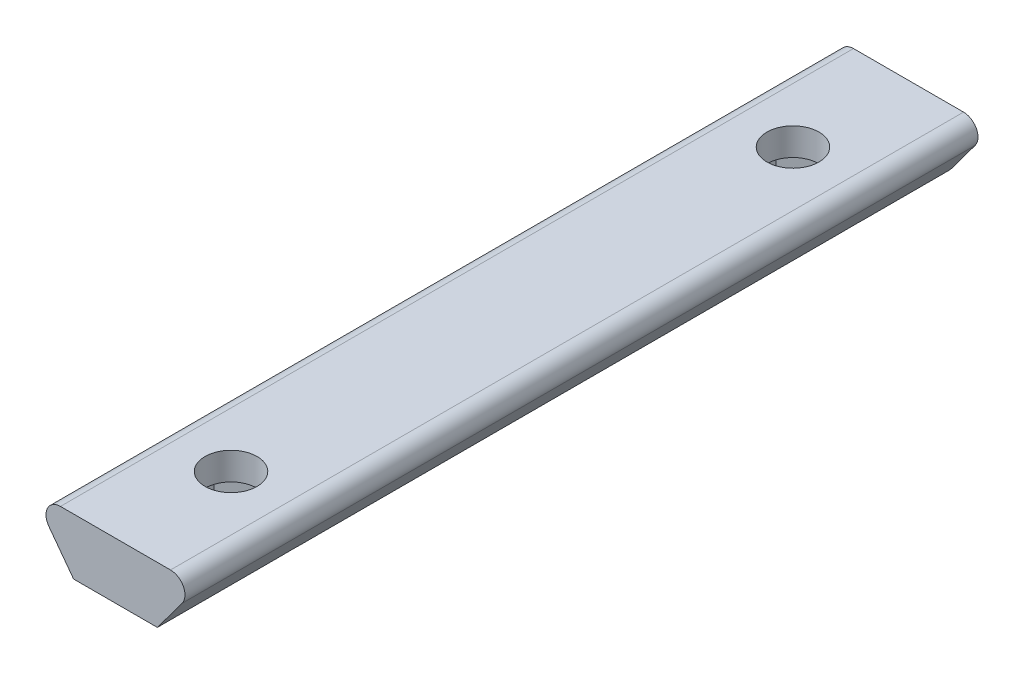
SolidWorks part; units mm, degrees
ref_plane "Front Plane" through (0, 0, 0) normal (0, 0, 1) x (1, 0, 0)
ref_plane "Top Plane" through (0, 0, 0) normal (0, 1, 0) x (1, 0, 0)
ref_plane "Right Plane" through (0, 0, 0) normal (1, 0, 0) x (0, 0, -1)
sketch "Sketch1" plane through (0, 0, 0) normal (0, 0, 1) x (1, 0, 0)
  line L0 (0, 0) -> (5.8, 0)
  line L1 (-2.9, 3.9) -> (8.7, 3.9)
  line L2 (0, 0) -> (-2.9, 3.9)
  line L3 (5.8, 0) -> (8.7, 3.9)
  dimension "D1" = 11.6
  dimension "D2" = 3.9
  dimension "D3" = 5.8
  dimension "D4" = 2.9
extrude "Boss-Extrude1" add sketch "Sketch1" along normal blind 54.9
fillet "Fillet1" radius 1 2 edges at (-2.9, 3.9, 27.45) (8.7, 3.9, 27.45)
sketch "Sketch2" plane through (0, 0, 0) normal (0, -1, 0) x (1, 0, 0)
  line L0 (2.9, 54.9) -> (2.9, 46.9) construction
  line L1 (0, 54.9) -> (5.8, 54.9) construction
  circle A0 centre (2.9, 46.9) radius 1.8
  dimension "D2" = 3.6
  dimension "D1" = 8
extrude "Cut-Extrude1" cut sketch "Sketch2" against normal blind 200
sketch "Sketch3" plane through (0, 0, 0) normal (0, -1, 0) x (1, 0, 0)
  line L1 (2.9397, 43.5516) -> (5.8196, 45.2602)
  line L2 (5.8196, 45.2602) -> (5.78, 48.6086)
  line L3 (5.78, 48.6086) -> (2.8603, 50.2484)
  line L4 (2.8603, 50.2484) -> (-0.0196, 48.5398)
  line L5 (-0.0196, 48.5398) -> (0.02, 45.1914)
  line L6 (0.02, 45.1914) -> (2.9397, 43.5516)
  circle A0 centre (2.9, 46.9) radius 2.9 construction
  dimension "D1" = 5.8
extrude "Cut-Extrude2" cut sketch "Sketch3" against normal blind 2
pattern_linear "LPattern1" count 2 spacing 38.9 along (0, 0, -1) of "Cut-Extrude1", "Cut-Extrude2"
